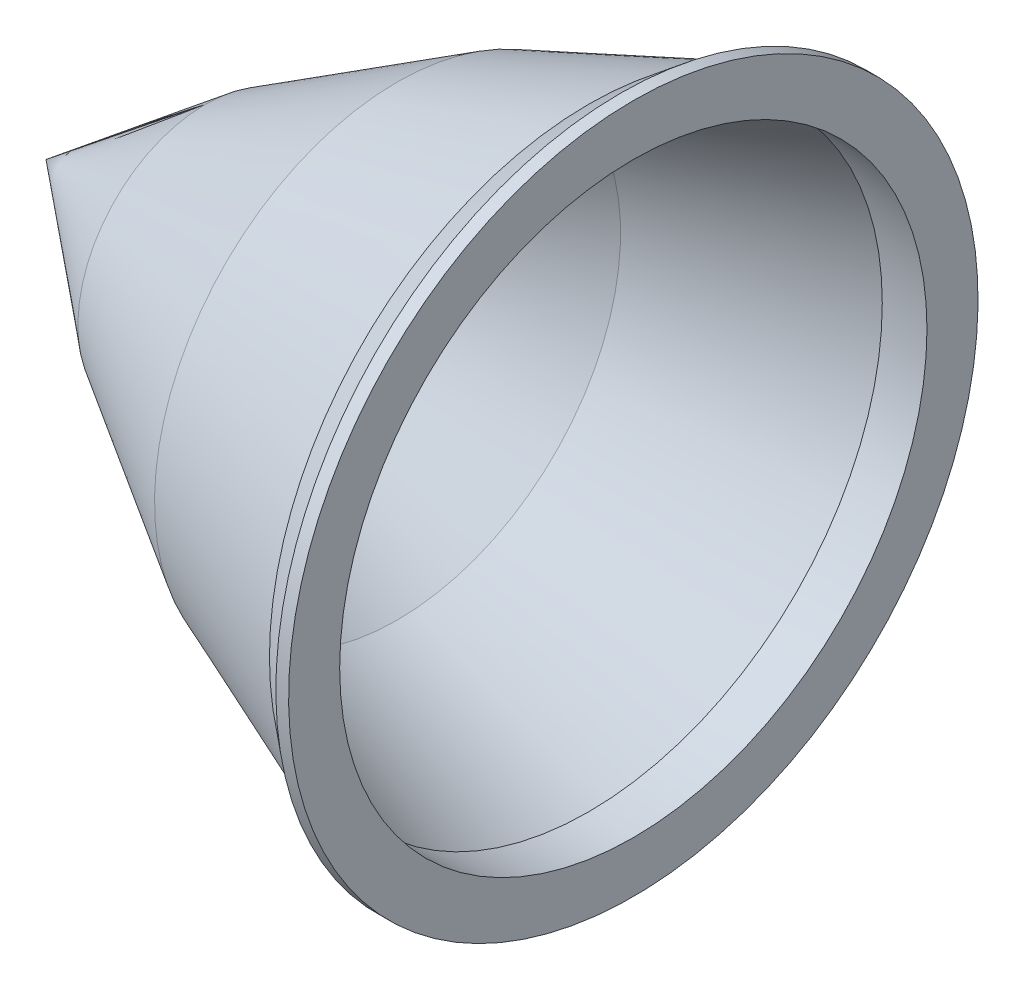
SolidWorks part; units mm, degrees
ref_plane "Front Plane" through (0, 0, 0) normal (0, 0, 1) x (1, 0, 0)
ref_plane "Top Plane" through (0, 0, 0) normal (0, 1, 0) x (1, 0, 0)
ref_plane "Right Plane" through (0, 0, 0) normal (1, 0, 0) x (0, 0, -1)
sketch "Sketch1" plane through (0, 0, 0) normal (0, 0, 1) x (1, 0, 0)
  line L0 (0, 0) -> (1200, 0) construction
  line L1 (0, 0) -> (250, 200)
  line L2 (250, 200) -> (550, 380)
  line L3 (550, 380) -> (850, 500)
  line L4 (850, 500) -> (900, 540)
  line L5 (900, 540) -> (920, 540)
  line L6 (920, 540) -> (920, 460)
  line L7 (920, 460) -> (850, 460)
  line L8 (850, 460) -> (550, 350)
  line L9 (550, 350) -> (250, 170)
  line L10 (250, 170) -> (50, 0)
  line L11 (50, 0) -> (0, 0)
revolve "Revolve1" add sketch "Sketch1" angle 360 about L0
